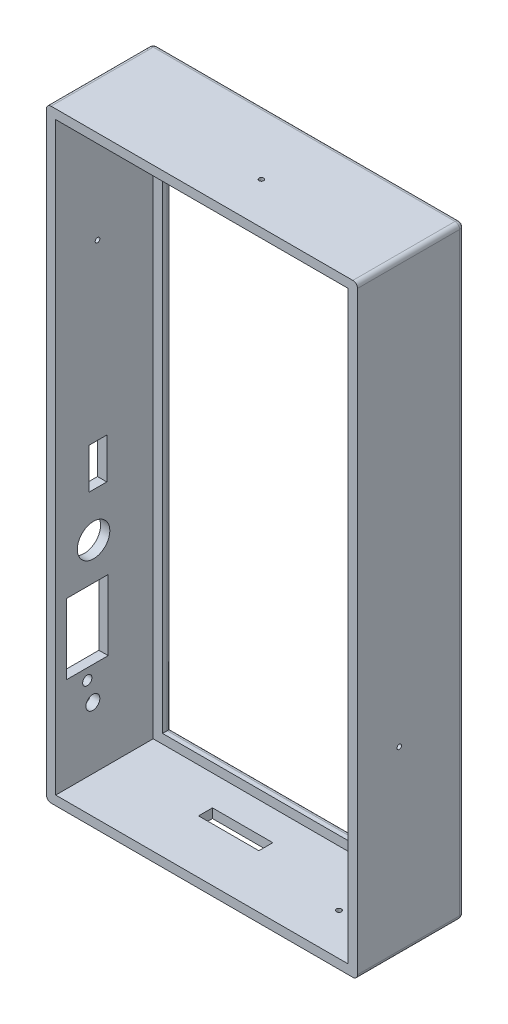
SolidWorks part; units mm, degrees
ref_plane "Piano frontale" through (0, 0, 0) normal (0, 0, 1) x (1, 0, 0)
ref_plane "Piano superiore" through (0, 0, 0) normal (0, 1, 0) x (1, 0, 0)
ref_plane "Piano destro" through (0, 0, 0) normal (1, 0, 0) x (0, 0, -1)
sketch "Schizzo1" plane through (0, 0, 0) normal (0, 0, 1) x (1, 0, 0)
  line L1 (-33.5, 65) -> (33.5, 65)
  line L2 (-33.5, 65) -> (-33.5, -65)
  line L3 (-33.5, -65) -> (33.5, -65)
  line L4 (33.5, 65) -> (33.5, -65)
  line L5 (-33.5, 65) -> (33.5, -65) construction
  line L6 (-33.5, -65) -> (33.5, 65) construction
  point P0 (0, 0)
  dimension "D1" = 130
  dimension "D2" = 67
extrude "Estrusione-Estrusione1" add sketch "Schizzo1" along normal blind 23
sketch "Schizzo2" plane through (0, 0, 23) normal (0, 0, 1) x (1, 0, 0)
  line L0 (-33.5, 65) -> (-33.5, -65) construction
  line L1 (-31.5, 63) -> (31.5, 63)
  line L2 (-31.5, 63) -> (-31.5, -63)
  line L3 (-31.5, -63) -> (31.5, -63)
  line L4 (31.5, 63) -> (31.5, -63)
  line L5 (-31.5, 63) -> (31.5, -63) construction
  line L6 (-31.5, -63) -> (31.5, 63) construction
  line L7 (33.5, 65) -> (-33.5, 65) construction
  point P0 (0, 0)
  dimension "D1" = 2
  dimension "D2" = 2
extrude "Taglio-Estrusione1" cut sketch "Schizzo2" against normal blind 21
sketch "Schizzo3" plane through (0, 0, 2) normal (0, 0, 1) x (1, 0, 0)
  line L0 (31.5, 63) -> (-31.5, 63) construction
  line L1 (-29.5, 61) -> (29.5, 61)
  line L2 (-29.5, 61) -> (-29.5, -61)
  line L3 (-29.5, -61) -> (29.5, -61)
  line L4 (29.5, 61) -> (29.5, -61)
  line L5 (-29.5, 61) -> (29.5, -61) construction
  line L6 (-29.5, -61) -> (29.5, 61) construction
  line L7 (31.5, -63) -> (31.5, 63) construction
  point P0 (0, 0)
  dimension "D1" = 2
  dimension "D2" = 2
extrude "Taglio-Estrusione2" cut sketch "Schizzo3" against normal through all both and the other way through all
other "Sposta faccia1" face at (-33.5, 0, 11.5) parameters "D1"=90
sketch "Schizzo4" plane through (-33.5, 0, 0) normal (-1, 0, 0) x (0, 0, 1)
  line L1 (20.7, -27.5) -> (11.7, -27.5)
  line L2 (20.7, -27.5) -> (20.7, -42.64)
  line L3 (20.7, -42.64) -> (11.7, -42.64)
  line L4 (11.7, -27.5) -> (11.7, -42.64)
  line L5 (15.83, -1.34) -> (12, -1.34)
  line L6 (15.83, -1.34) -> (15.83, -10.09)
  line L7 (15.83, -10.09) -> (12, -10.09)
  line L8 (12, -1.34) -> (12, -10.09)
  line L9 (0, 65) -> (0, -65) construction
  line L10 (16.2, -42.64) -> (16.2, -44.9925) construction
  line L12 (23, 65) -> (0, 65) construction
  circle A0 centre (15, -49.7) radius 1.5
  circle A1 centre (14.85, -19.5) radius 3.5
  circle A2 centre (16.2, -44.9925) radius 1
  point P22 (11.5, 65)
  dimension "D2" = 84.5
  dimension "D4" = 114.7
  dimension "D12" = 7
  dimension "D13" = 3
  dimension "D14" = 2
  dimension "D16" = 15
  dimension "D3" = 92.5
  dimension "D5" = 12
  dimension "D6" = 14.85
  dimension "D7" = 3.83
  dimension "D8" = 8.75
  dimension "D9" = 9
  dimension "D10" = 15.14
  dimension "D11" = 11.7
  dimension "D15" = 66.34
extrude "Taglio-Estrusione4" cut sketch "Schizzo4" against normal up to next
sketch "Schizzo5" plane through (0, -65, 0) normal (0, -1, 0) x (1, 0, 0)
  line L0 (-33.5, 0) -> (33.5, 0) construction
  line L1 (-12.2415, 11.5) -> (0.7585, 11.5)
  line L2 (-12.2415, 11.5) -> (-12.2415, 8.5)
  line L3 (-12.2415, 8.5) -> (0.7585, 8.5)
  line L4 (0.7585, 11.5) -> (0.7585, 8.5)
  line L5 (-12.2415, 11.5) -> (0.7585, 8.5) construction
  line L6 (-12.2415, 8.5) -> (0.7585, 11.5) construction
  point P0 (-5.7415, 10)
  dimension "D1" = 13
  dimension "D2" = 3
  dimension "D3" = 8.5
extrude "Taglio-Estrusione5" cut sketch "Schizzo5" against normal up to next
fillet "Raccordo1" radius 1 12 edges at (0, 65, 0) (-33.5, 0, 0) (0, -65, 0) (33.5, 0, 0) (-29.5, 0, 0) (0, 61, 0) (29.5, 0, 0) (0, -61, 0) (-33.5, -65, 11.5) (33.5, -65, 11.5) (33.5, 65, 11.5) (-33.5, 65, 11.5)
sketch "Schizzo6" plane through (33.5, 0, 0) normal (1, 0, 0) x (0, 0, -1)
  line L1 (-23, -64) -> (-23, 64) construction
  line L2 (-23, -64) -> (-1, -64) construction
  circle A0 centre (-14, -26) radius 0.5
  dimension "D1" = 9
  dimension "D2" = 38
extrude "Taglio-Estrusione6" cut sketch "Schizzo6" against normal up to next
sketch "Schizzo7" plane through (0, 65, 0) normal (0, 1, 0) x (1, 0, 0)
  line L2 (32.5, -23) -> (32.5, -1) construction
  line L3 (32.5, -23) -> (-32.5, -23) construction
  circle A0 centre (3.81, -14) radius 0.5
  dimension "D1" = 9
  dimension "D2" = 28.69
extrude "Taglio-Estrusione7" cut sketch "Schizzo7" against normal blind 10
sketch "Schizzo8" plane through (-33.5, 0, 0) normal (-1, 0, 0) x (0, 0, 1)
  line L0 (23, 64) -> (1, 64) construction
  line L2 (23, 64) -> (23, -64) construction
  circle A0 centre (14, 36) radius 0.5
  dimension "D1" = 28
  dimension "D2" = 9
extrude "Taglio-Estrusione8" cut sketch "Schizzo8" against normal blind 10
sketch "Schizzo9" plane through (0, -65, 0) normal (0, -1, 0) x (1, 0, 0)
  line L0 (-32.5, 23) -> (32.5, 23) construction
  line L1 (32.5, 1) -> (32.5, 23) construction
  circle A0 centre (20.5, 14) radius 0.54
  dimension "D1" = 9
  dimension "D2" = 12
extrude "Taglio-Estrusione9" cut sketch "Schizzo9" against normal blind 10
